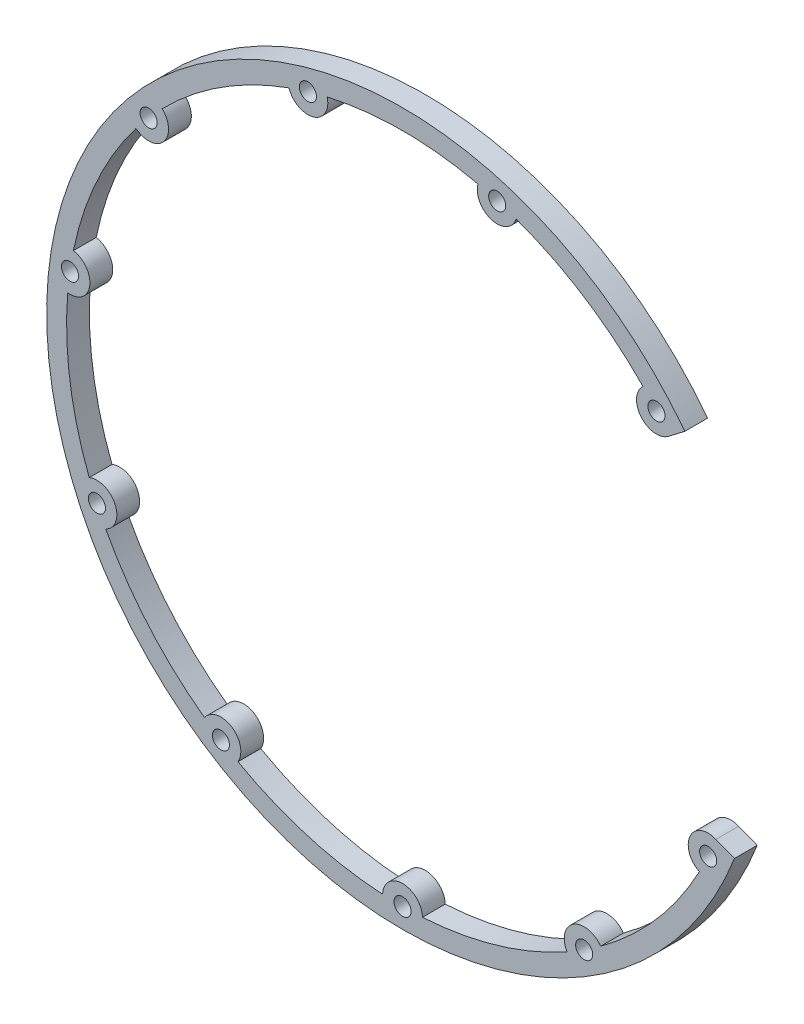
SolidWorks part; units mm, degrees
ref_plane "前视基准面" through (0, 0, 0) normal (0, 0, 1) x (1, 0, 0)
ref_plane "上视基准面" through (0, 0, 0) normal (0, 1, 0) x (1, 0, 0)
ref_plane "右视基准面" through (0, 0, 0) normal (1, 0, 0) x (0, 0, -1)
sketch "草图1" plane through (0, 0, 0) normal (0, 0, 1) x (1, 0, 0)
  line L0 (0, -59) -> (0, 0) construction
  line L1 (0, 0) -> (21.3581, 0) construction
  line L2 (46.8018, 35.9248) -> (49.5781, 38.056)
  line L3 (55.0272, -21.284) -> (58.2915, -22.5467)
  circle A1 centre (0, 0) radius 62.5 construction
  circle A2 centre (0, 0) radius 59 construction
  circle A3 centre (0, -59) radius 1.5
  circle A4 centre (0, -59) radius 3.5 construction
  arc A5 (3.4985, -58.8962) -> (-3.4985, -58.8962) centre (0, -59) ccw
  circle A6 centre (-31.8978, -49.634) radius 1.5
  circle A7 centre (-53.6683, -24.5095) radius 1.5
  circle A8 centre (-58.3995, 8.3966) radius 1.5
  circle A9 centre (-44.5892, 38.6368) radius 1.5
  circle A10 centre (-16.6222, 56.6101) radius 1.5
  circle A11 centre (16.6222, 56.6101) radius 1.5
  circle A12 centre (44.5892, 38.6368) radius 1.5
  circle A13 centre (58.3995, 8.3966) radius 1.5 construction
  circle A14 centre (53.6683, -24.5095) radius 1.5
  circle A15 centre (31.8978, -49.634) radius 1.5
  circle A16 centre (31.8978, -49.634) radius 3.5 construction
  arc A17 (28.8986, -51.438) -> (3.4985, -58.8962) centre (0, 0) cw
  arc A18 (-3.4985, -58.8962) -> (-28.8986, -51.438) centre (0, 0) cw
  arc A19 (-28.8986, -51.438) -> (-34.7848, -47.6552) centre (-31.8978, -49.634) ccw
  arc A20 (-34.7848, -47.6552) -> (-52.1205, -27.6487) centre (0, 0) cw
  arc A21 (-52.1205, -27.6487) -> (-55.0272, -21.284) centre (-53.6683, -24.5095) ccw
  arc A22 (-55.0272, -21.284) -> (-58.7946, 4.919) centre (0, 0) cw
  arc A23 (-58.7946, 4.919) -> (-57.7988, 11.8447) centre (-58.3995, 8.3966) ccw
  arc A24 (-57.7988, 11.8447) -> (-46.8018, 35.9248) centre (0, 0) cw
  arc A25 (-46.8018, 35.9248) -> (-42.2198, 41.2128) centre (-44.5892, 38.6368) ccw
  arc A26 (-42.2198, 41.2128) -> (-19.9497, 55.5248) centre (0, 0) cw
  arc A27 (-19.9497, 55.5248) -> (-13.2362, 57.4961) centre (-16.6222, 56.6101) ccw
  arc A28 (-13.2362, 57.4961) -> (13.2362, 57.4961) centre (0, 0) cw
  arc A29 (13.2362, 57.4961) -> (19.9497, 55.5248) centre (16.6222, 56.6101) ccw
  arc A30 (19.9497, 55.5248) -> (42.2198, 41.2128) centre (0, 0) cw
  arc A31 (42.2198, 41.2128) -> (46.8018, 35.9248) centre (44.5892, 38.6368) ccw
  arc A32 (46.8018, 35.9248) -> (57.7988, 11.8447) centre (0, 0) cw construction
  arc A33 (57.7988, 11.8447) -> (58.7946, 4.919) centre (58.3995, 8.3966) ccw construction
  arc A34 (58.7946, 4.919) -> (55.0272, -21.284) centre (0, 0) cw construction
  arc A35 (55.0272, -21.284) -> (52.1205, -27.6487) centre (53.6683, -24.5095) ccw
  arc A36 (52.1205, -27.6487) -> (34.7848, -47.6552) centre (0, 0) cw
  arc A37 (34.7848, -47.6552) -> (28.8986, -51.438) centre (31.8978, -49.634) ccw
  arc A38 (49.5781, 38.056) -> (58.2915, -22.5467) centre (0, 0) ccw
  point P7 (0, 0)
  dimension "D1" = 11
  dimension "D2" = 125
  dimension "D3" = 118
  dimension "D4" = 3
  dimension "D5" = 11
extrude "凸台-拉伸1" add sketch "草图1" along normal blind 4 contours A4
